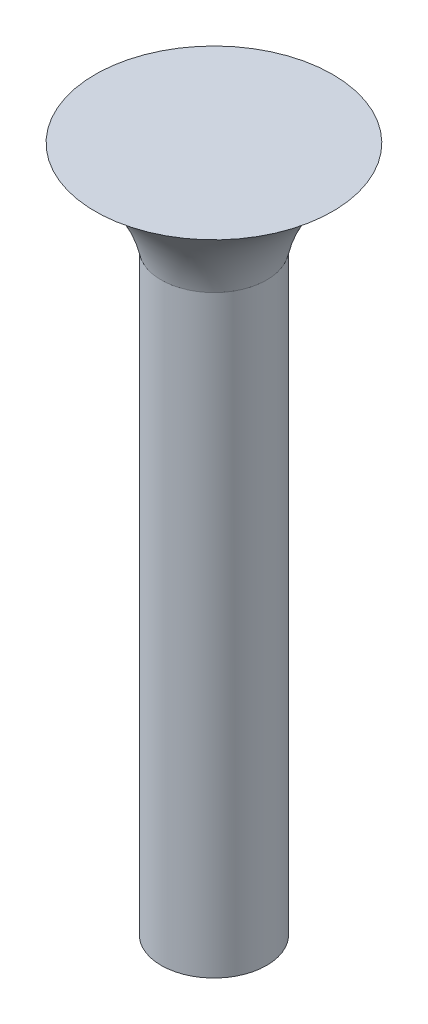
SolidWorks part; units mm, degrees
ref_plane "Front Plane" through (0, 0, 0) normal (0, 0, 1) x (1, 0, 0)
ref_plane "Top Plane" through (0, 0, 0) normal (0, 1, 0) x (1, 0, 0)
ref_plane "Right Plane" through (0, 0, 0) normal (1, 0, 0) x (0, 0, -1)
sketch "Sketch1" plane through (0, 0, 0) normal (0, 1, 0) x (1, 0, 0)
  circle A0 centre (0, 0) radius 10.16
  dimension "D1" = 20.32
extrude "Boss-Extrude1" add sketch "Sketch1" along normal blind 132.08
sketch "Sketch2" plane through (0, 0, 0) normal (0, 0, 1) x (1, 0, 0)
  line L0 (10.16, 132.08) -> (10.16, 114.3)
  line L1 (10.16, 132.08) -> (22.86, 132.08)
  line L2 (0, 0) -> (0, 49.4686) construction
  arc A0 (22.86, 132.08) -> (10.16, 114.3) centre (36.6036, 108.8374) ccw
  dimension "D1" = 17.78
  dimension "D2" = 12.7
revolve "Revolve1" add sketch "Sketch2" angle 360 about L2
